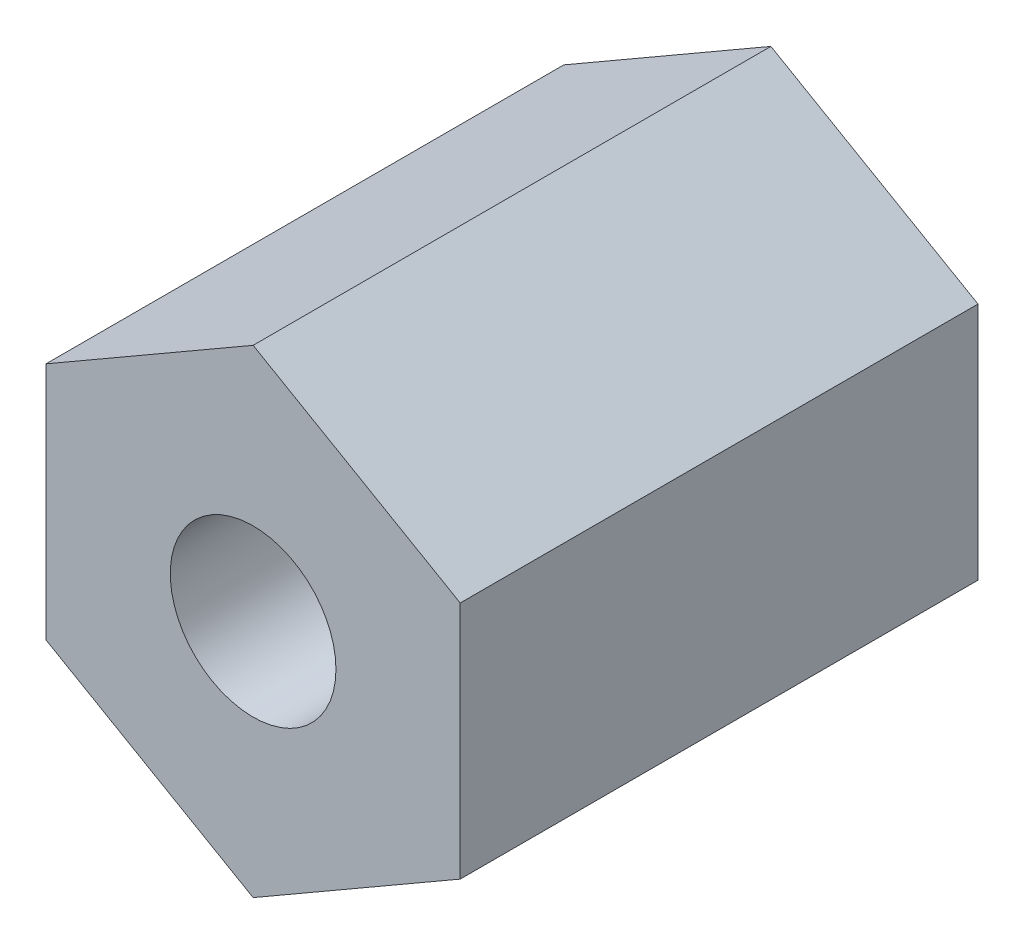
SolidWorks part; units mm, degrees
ref_plane "前视基准面" through (0, 0, 0) normal (0, 0, 1) x (1, 0, 0)
ref_plane "上视基准面" through (0, 0, 0) normal (0, 1, 0) x (1, 0, 0)
ref_plane "右视基准面" through (0, 0, 0) normal (1, 0, 0) x (0, 0, -1)
other "Configuration Table"
sketch "草图1" plane through (0, 0, 0) normal (0, 0, 1) x (1, 0, 0)
  line L0 (2, 1.1547) -> (0, 2.3094)
  line L1 (0, 2.3094) -> (-2, 1.1547)
  line L2 (-2, 1.1547) -> (-2, -1.1547)
  line L3 (-2, -1.1547) -> (0, -2.3094)
  line L4 (0, -2.3094) -> (2, -1.1547)
  line L5 (2, -1.1547) -> (2, 1.1547)
  circle A0 centre (0, 0) radius 0.8
extrude "Brass_AF4_L5_M2" add sketch "草图1" along normal blind 5
